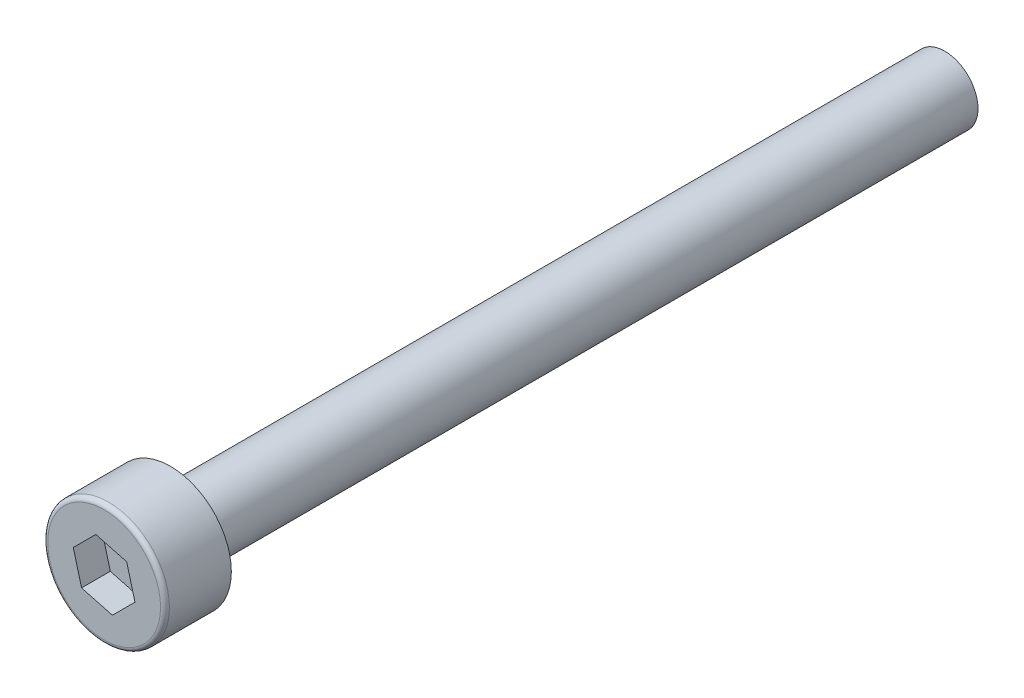
SolidWorks part; units mm, degrees
ref_plane "前视基准面" through (0, 0, 0) normal (0, 0, 1) x (1, 0, 0)
ref_plane "上视基准面" through (0, 0, 0) normal (0, 1, 0) x (1, 0, 0)
ref_plane "右视基准面" through (0, 0, 0) normal (1, 0, 0) x (0, 0, -1)
sketch "草图1" plane through (0, 0, 0) normal (0, 0, 1) x (1, 0, 0)
  circle A0 centre (0, 0) radius 2.75
  dimension "D1" = 5.5
extrude "凸台-拉伸1" add sketch "草图1" along normal blind 3
sketch "草图2" plane through (0, 0, 3) normal (0, 0, 1) x (1, 0, 0)
  line L1 (-1.0206, -1.0206) -> (0.3736, -1.3942)
  line L2 (0.3736, -1.3942) -> (1.3942, -0.3736)
  line L3 (1.3942, -0.3736) -> (1.0206, 1.0206)
  line L4 (1.0206, 1.0206) -> (-0.3736, 1.3942)
  line L5 (-0.3736, 1.3942) -> (-1.3942, 0.3736)
  line L6 (-1.3942, 0.3736) -> (-1.0206, -1.0206)
  circle A0 centre (0, 0) radius 1.25 construction
  dimension "D1" = 2.5
extrude "切除-拉伸1" cut sketch "草图2" against normal blind 1.3
sketch "草图3" plane through (0, 0, 0) normal (0, 0, -1) x (-1, 0, 0)
  circle A0 centre (0, 0) radius 1.5
  dimension "D1" = 3
extrude "凸台-拉伸2" add sketch "草图3" along normal blind 35
fillet "圆角1" radius 0.2 1 edges at (2.75, 0, 3)
